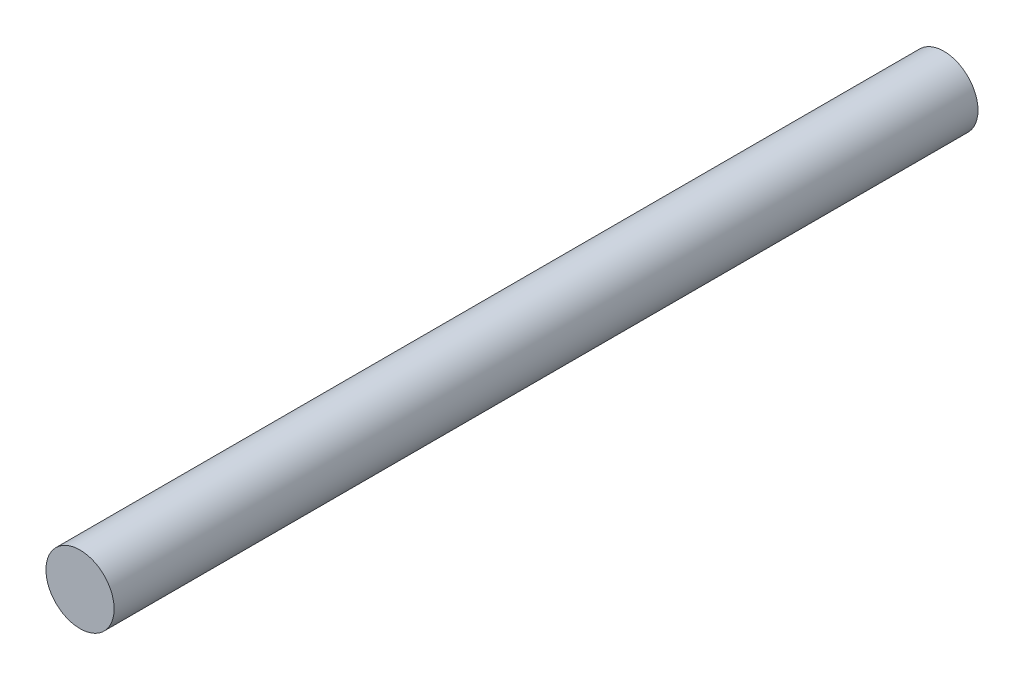
SolidWorks part; units mm, degrees
ref_plane "Front Plane" through (0, 0, 0) normal (0, 0, 1) x (1, 0, 0)
ref_plane "Top Plane" through (0, 0, 0) normal (0, 1, 0) x (1, 0, 0)
ref_plane "Right Plane" through (0, 0, 0) normal (1, 0, 0) x (0, 0, -1)
sketch "Sketch1" plane through (0, 0, 0) normal (0, 0, 1) x (1, 0, 0)
  circle A0 centre (0, 0) radius 1.5
  dimension "D1" = 3
extrude "Boss-Extrude1" add sketch "Sketch1" along normal blind 38
